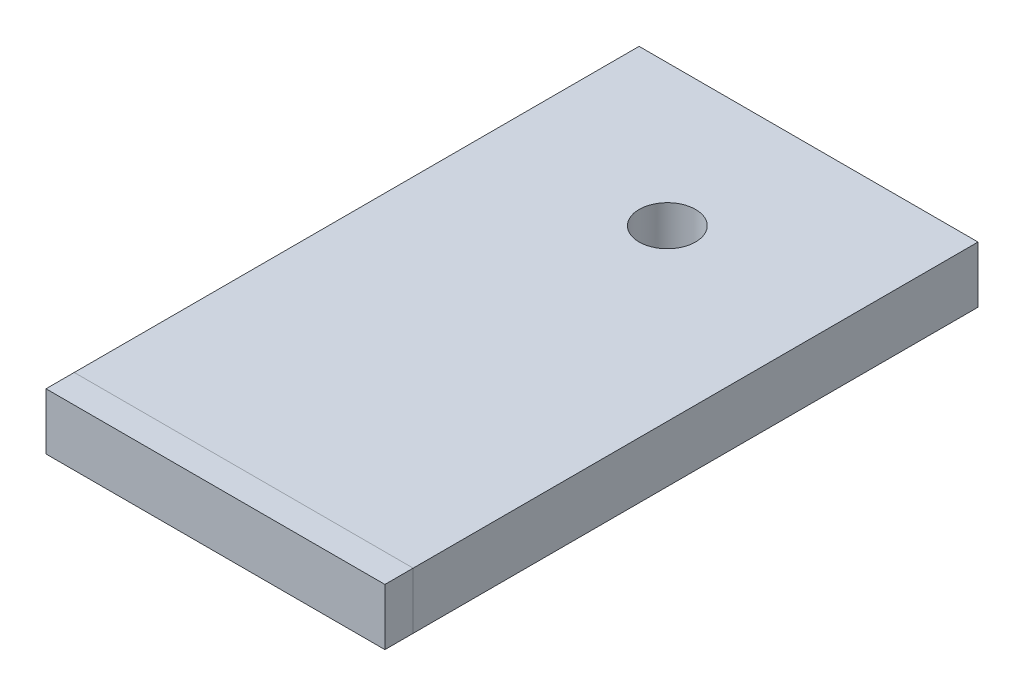
SolidWorks part; units mm, degrees
material "Maple"
ref_plane "Front Plane" through (0, 0, 0) normal (0, 0, 1) x (1, 0, 0)
ref_plane "Top Plane" through (0, 0, 0) normal (0, 1, 0) x (1, 0, 0)
ref_plane "Right Plane" through (0, 0, 0) normal (1, 0, 0) x (0, 0, -1)
sketch "Sketch1" plane through (0, 0, 0) normal (0, 1, 0) x (1, 0, 0)
  line L1 (-38.1, 63.5) -> (38.1, 63.5)
  line L2 (-38.1, 63.5) -> (-38.1, -63.5)
  line L3 (-38.1, -63.5) -> (38.1, -63.5)
  line L4 (38.1, 63.5) -> (38.1, -63.5)
  line L5 (-38.1, 63.5) -> (38.1, -63.5) construction
  line L6 (-38.1, -63.5) -> (38.1, 63.5) construction
  point P0 (0, 0)
  dimension "D1" = 76.2
  dimension "D2" = 127
extrude "Boss-Extrude1" add sketch "Sketch1" along normal blind 19.05
sketch "Sketch2" plane through (0, 19.05, 0) normal (0, 1, 0) x (1, 0, 0)
  line L0 (-38.1, -63.5) -> (38.1, -63.5) construction
  circle A0 centre (0, 31.75) radius 6.35
  dimension "D1" = 12.7
  dimension "D2" = 95.25
extrude "Cut-Extrude1" cut sketch "Sketch2" against normal through all
sketch "Sketch3" plane through (0, 0, 63.5) normal (0, 0, 1) x (1, 0, 0)
  line L1 (-38.1, 19.05) -> (38.1, 19.05)
  line L2 (-38.1, 19.05) -> (-38.1, 0)
  line L3 (-38.1, 0) -> (38.1, 0)
  line L4 (38.1, 19.05) -> (38.1, 0)
  line L5 (-38.1, 19.05) -> (38.1, 0) construction
  line L6 (-38.1, 0) -> (38.1, 19.05) construction
  point P0 (0, 9.525)
extrude "Boss-Extrude2" add sketch "Sketch3" along normal blind 6.35 separate body
sketch "Sketch4" plane through (0, 0, -63.5) normal (0, 0, -1) x (-1, 0, 0)
  line L0 (-4.3656, 0) -> (4.3656, 0) construction
  line L1 (-38.1, 0) -> (-4.3656, 0)
  line L2 (-38.1, 0) -> (-38.1, 6.35)
  line L3 (-38.1, 6.35) -> (-4.3656, 6.35)
  line L4 (-4.3656, 0) -> (-4.3656, 6.35)
  line L5 (4.3656, 6.35) -> (38.1, 6.35)
  line L6 (4.3656, 6.35) -> (4.3656, 0)
  line L7 (4.3656, 0) -> (38.1, 0)
  line L8 (38.1, 6.35) -> (38.1, 0)
  dimension "D1" = 6.35
  dimension "D2" = 8.7312
extrude "Cut-Extrude2" cut sketch "Sketch4" against normal through all
sketch "Sketch5" plane through (0, 0, 69.85) normal (0, 0, 1) x (1, 0, 0)
  line L1 (-4.3656, 6.35) -> (4.3656, 6.35)
  line L2 (-4.3656, 6.35) -> (-4.3656, 0)
  line L3 (-4.3656, 0) -> (4.3656, 0)
  line L4 (4.3656, 6.35) -> (4.3656, 0)
extrude "Cut-Extrude3" cut sketch "Sketch5" against normal up to vertex (6.35 mm away)
